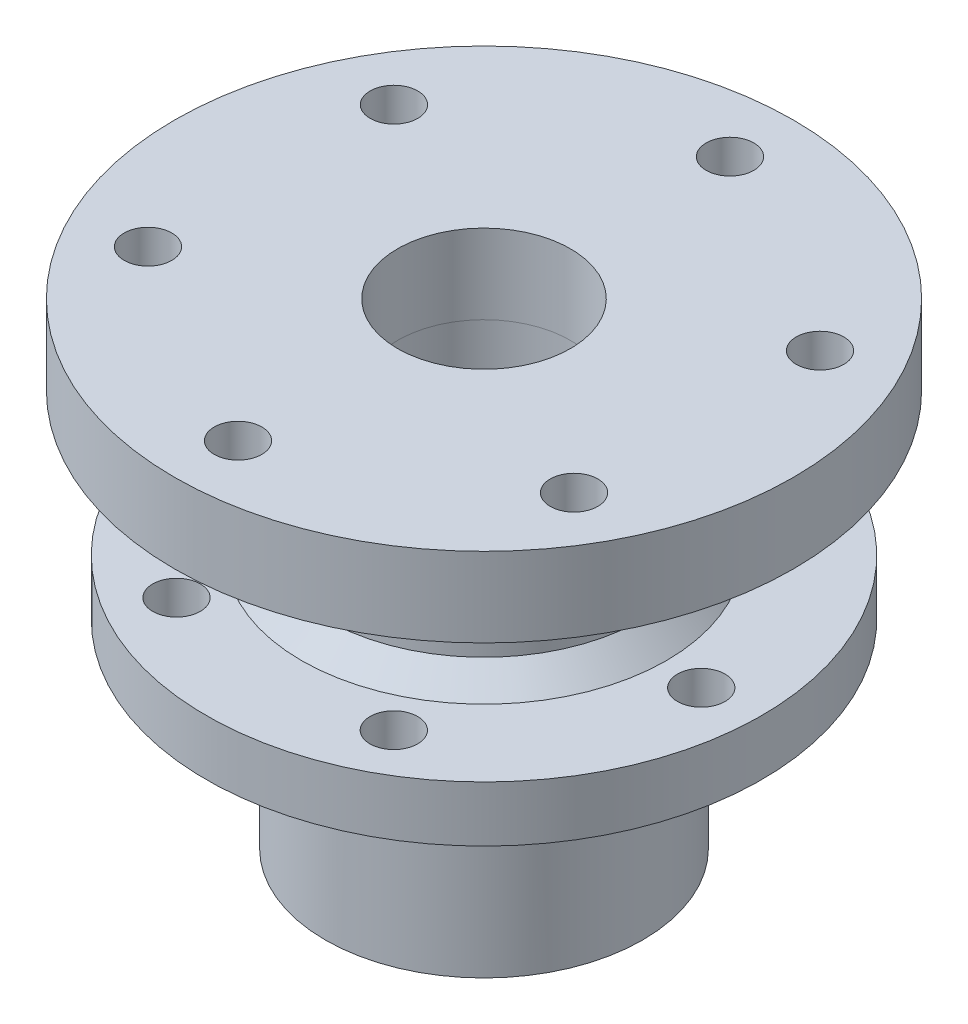
SolidWorks part; units mm, degrees
ref_plane "Спереди" through (0, 0, 0) normal (0, 0, 1) x (1, 0, 0)
ref_plane "Сверху" through (0, 0, 0) normal (0, 1, 0) x (1, 0, 0)
ref_plane "Справа" through (0, 0, 0) normal (1, 0, 0) x (0, 0, -1)
sketch "Эскиз1" plane through (0, 0, 0) normal (0, 1, 0) x (1, 0, 0)
  circle A0 centre (0, 0) radius 11
  circle A1 centre (0, 0) radius 20
extrude "Вытянуть1" add sketch "Эскиз1" along normal blind 50 from offset 10 offset against normal yes
sketch "Эскиз2" plane through (0, 40, 0) normal (0, 1, 0) x (1, 0, 0)
  circle A0 centre (0, 0) radius 10.9
  circle A1 centre (0, 0) radius 39
extrude "Вытянуть2" add sketch "Эскиз2" along normal blind 10
chamfer "Фаска1" distance 4 angle 45 1 edges at (0, 40, 20)
ref_plane "Плоскость1" through (0, 15, 0) normal (0, -1, 0) x (1, 0, 0)
sketch "Эскиз3" plane through (0, 15, 0) normal (0, -1, 0) x (1, 0, 0)
  circle A0 centre (0, 0) radius 17
  circle A1 centre (0, 0) radius 35
extrude "Вытянуть3" add sketch "Эскиз3" against normal blind 7
chamfer "Фаска2" distance 3 angle 45 1 edges at (0, 22, -20)
sketch "Эскиз4" plane through (0, 22, 0) normal (0, 1, 0) x (1, 0, 0)
  circle A0 centre (-13.4138, 24.7584) radius 3
  circle A1 centre (14.7426, 23.9909) radius 3
  circle A2 centre (28.1561, -0.777) radius 3
  circle A3 centre (13.4132, -24.7774) radius 3
  circle A4 centre (-14.7431, -24.0099) radius 3
  circle A5 centre (-28.1567, 0.758) radius 3
extrude "Вырез-Вытянуть1" cut sketch "Эскиз4" against normal through all
sketch "Эскиз5" plane through (0, 50, 0) normal (0, 1, 0) x (1, 0, 0)
  circle A0 centre (0, 31) radius 3
  circle A1 centre (26.8468, 15.5) radius 3
  circle A2 centre (26.8468, -15.5) radius 3
  circle A3 centre (0, -31) radius 3
  circle A4 centre (-26.8468, -15.5) radius 3
  circle A5 centre (-26.8468, 15.5) radius 3
  dimension "D1" = 31
extrude "Вытянуть4" cut sketch "Эскиз5" against normal up to next
